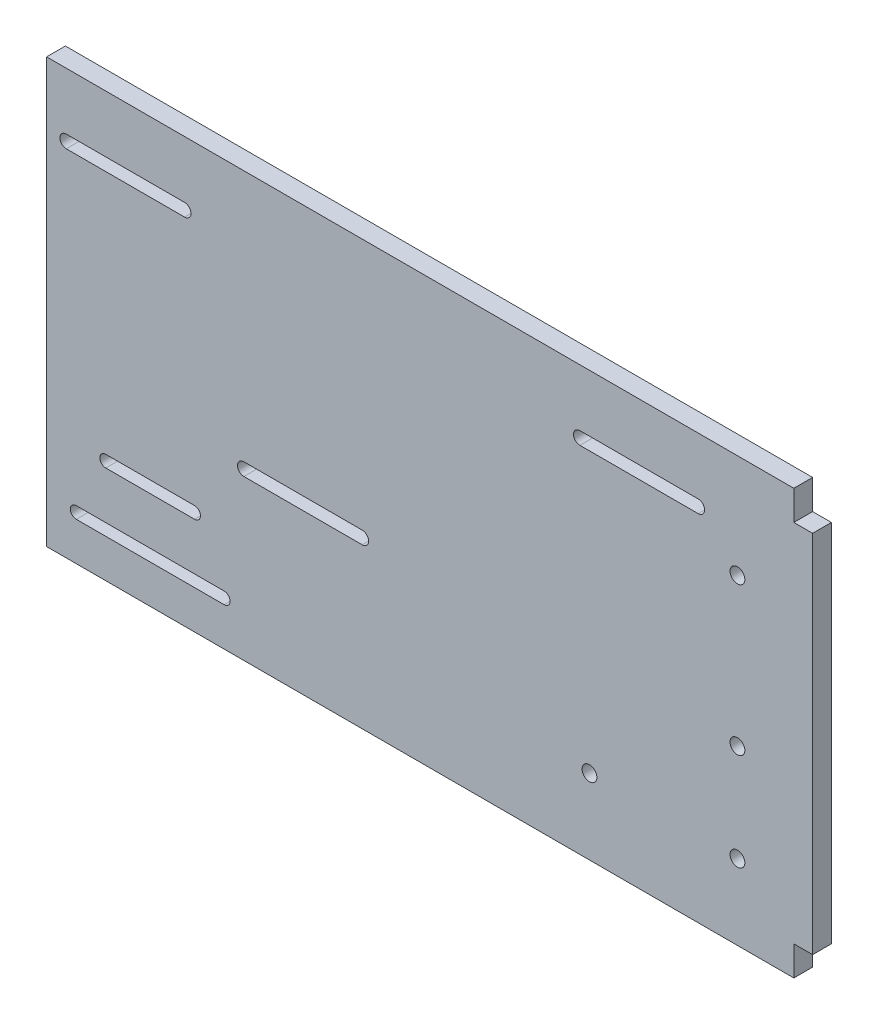
SolidWorks part; units mm, degrees
ref_plane "Front Plane" through (0, 0, 0) normal (0, 0, 1) x (1, 0, 0)
ref_plane "Top Plane" through (0, 0, 0) normal (0, 1, 0) x (1, 0, 0)
ref_plane "Right Plane" through (0, 0, 0) normal (1, 0, 0) x (0, 0, -1)
sketch "Sketch1" plane through (0, 0, 0) normal (0, 0, 1) x (1, 0, 0)
  line L6 (201.8749, 11.6995) -> (153.9614, -58.0745)
  line L7 (-16.8983, 41.9627) -> (201.8749, 41.9627)
  line L8 (-16.8983, 41.9627) -> (-16.8983, -41.404)
  line L9 (67.0768, -58.0745) -> (153.9614, -58.0745)
  line L10 (201.8749, 41.9627) -> (201.8749, 11.6995)
  line L11 (-16.8983, -41.404) -> (67.0768, -41.404)
  line L12 (67.0768, -58.0745) -> (67.0768, -41.404)
  line L13 (235.9349, 52.2529) -> (235.9349, -6.9018) construction
  circle A3 centre (18.7386, 20.5357) radius 2.15
  circle A4 centre (192.2886, 20.5357) radius 2.15
  circle A5 centre (78.7486, -45.3543) radius 2.15
  point P14 (-16.8983, -209.404)
  point P21 (17.0917, -18.834)
  dimension "D14" = 4.3
  dimension "D15" = 4.3
  dimension "D16" = 4.3
  dimension "D1" = 218.7732
  dimension "D2" = 83.3667
  dimension "D3" = 35.6369
  dimension "D4" = 209.1869
  dimension "D5" = 21.427
  dimension "D6" = 87.317
  dimension "D7" = 100.0372
  dimension "D8" = 83.9751
  dimension "D9" = 30.2632
  dimension "D10" = 86.8846
  dimension "D11" = 95.6469
  dimension "D12" = 22.57
  dimension "D13" = 33.99
  dimension "D17" = 34.06
  dimension "D18" = 21.427
  dimension "D19" = 168
sketch "Sketch3" plane through (0, 0, 0) normal (0, 0, 1) x (1, 0, 0)
  line L0 (235.9349, 52.2529) -> (235.9349, -6.9018) construction
  line L1 (235.9349, 52.2529) -> (235.9349, -6.9018) construction
  line L2 (58.7486, -43.2043) -> (98.7486, -43.2043)
  line L3 (244.5849, 41.9627) -> (-7.9083, 41.9627)
  line L4 (250.9349, 31.9627) -> (250.9349, -91.3543)
  line L5 (244.5849, -101.3543) -> (-7.9083, -101.3543)
  line L6 (-7.9083, 41.9627) -> (-7.9083, -101.3543)
  line L7 (17.0917, -86.3543) -> (37.0917, -86.3543) construction
  line L8 (-16.8983, 41.9627) -> (201.8749, 41.9627) construction
  line L9 (-1.2614, 22.6857) -> (38.7386, 22.6857)
  line L14 (-1.2614, 18.3857) -> (38.7386, 18.3857)
  line L15 (58.7486, -47.5043) -> (98.7486, -47.5043)
  line L16 (172.2886, 22.6857) -> (212.2886, 22.6857)
  line L17 (172.2886, 18.3857) -> (212.2886, 18.3857)
  line L18 (141.1766, -87.3543) -> (217.4403, -87.3543) construction
  line L19 (244.5849, 31.9586) -> (244.5849, -45.3543) construction
  line L20 (7.0917, -245.3543) -> (47.0917, -245.3543) construction
  line L21 (7.0917, -245.3543) -> (7.0917, -56.3543) construction
  line L22 (7.0917, -56.3543) -> (47.0917, -56.3543) construction
  line L23 (47.0917, -245.3543) -> (47.0917, -56.3543) construction
  line L24 (12.0917, -64.3543) -> (42.0917, -64.3543)
  line L25 (12.0917, -68.3543) -> (42.0917, -68.3543)
  line L40 (2.0917, -84.3543) -> (52.0917, -84.3543)
  line L41 (2.0917, -88.3543) -> (52.0917, -88.3543)
  line L45 (250.9349, 31.9627) -> (244.5849, 31.9627)
  line L46 (244.5849, 41.9627) -> (244.5849, 31.9627)
  line L49 (250.9349, -91.3543) -> (244.5849, -91.3543)
  line L50 (244.5849, -101.3543) -> (244.5849, -91.3543)
  circle A0 centre (78.7486, -45.3543) radius 2.15 construction
  circle A1 centre (192.2886, 20.5357) radius 2.15 construction
  circle A2 centre (18.7386, 20.5357) radius 2.15 construction
  circle A3 centre (78.7486, -45.3543) radius 2.15 construction
  circle A4 centre (192.2886, 20.5357) radius 2.15 construction
  circle A5 centre (18.7386, 20.5357) radius 2.15 construction
  arc A6 (-1.2614, 22.6857) -> (-1.2614, 18.3857) centre (-1.2614, 20.5357) ccw
  arc A7 (38.7386, 22.6857) -> (38.7386, 18.3857) centre (38.7386, 20.5357) cw
  arc A8 (58.7486, -43.2043) -> (58.7486, -47.5043) centre (58.7486, -45.3543) ccw
  arc A9 (98.7486, -43.2043) -> (98.7486, -47.5043) centre (98.7486, -45.3543) cw
  arc A10 (172.2886, 22.6857) -> (172.2886, 18.3857) centre (172.2886, 20.5357) ccw
  arc A11 (212.2886, 22.6857) -> (212.2886, 18.3857) centre (212.2886, 20.5357) cw
  circle A12 centre (17.0917, -86.3543) radius 2 construction
  circle A13 centre (37.0917, -86.3543) radius 2 construction
  circle A14 centre (27.0917, -66.3543) radius 2 construction
  circle A15 centre (225.5349, -43.0373) radius 2.5
  circle A17 centre (225.5349, 6.9627) radius 2.5
  circle A19 centre (225.5349, -75.9543) radius 2.5
  circle A21 centre (175.5349, -75.9543) radius 2.5
  arc A22 (12.0917, -68.3543) -> (12.0917, -64.3543) centre (12.0917, -66.3543) cw
  arc A23 (42.0917, -68.3543) -> (42.0917, -64.3543) centre (42.0917, -66.3543) ccw
  arc A24 (2.0917, -84.3543) -> (2.0917, -88.3543) centre (2.0917, -86.3543) ccw
  arc A25 (52.0917, -88.3543) -> (52.0917, -84.3543) centre (52.0917, -86.3543) ccw
  point P32 (18.7386, 18.3857)
  point P46 (192.2886, 22.6857)
  point P49 (78.7486, -43.2043)
  point P57 (17.0917, -18.834)
  point P62 (27.0917, -56.3543)
  point P65 (27.0917, -86.3543)
  point P70 (27.0917, -64.3543)
  dimension "D8" = 4
  dimension "D9" = 4
  dimension "D18" = 4
  dimension "D15" = 5
  dimension "D16" = 5
  dimension "D24" = 5
  dimension "D25" = 5
  dimension "D1" = 15
  dimension "D4" = 40
  dimension "D5" = 40
  dimension "D6" = 40
  dimension "D7" = 42
  dimension "D2" = 25
  dimension "D3" = 15
  dimension "D10" = 14
  dimension "D11" = 15
  dimension "D12" = 20
  dimension "D19" = 20
  dimension "D20" = 40
  dimension "D21" = 10
  dimension "D13" = 200
  dimension "D14" = 6.35
  dimension "D17" = 50
  dimension "D22" = 19.05
  dimension "D26" = 25.4
  dimension "D27" = 50
  dimension "D23" = 35
  dimension "D28" = 10
  dimension "D29" = 30
  dimension "D30" = 15
  dimension "D31" = 15
  dimension "D32" = 10
  dimension "D33" = 6.35
  dimension "D34" = 6.35
  dimension "D35" = 10
extrude "Boss-Extrude1" add sketch "Sketch3" along normal blind 6.35
equation "\"D15@Sketch1\"=\"D14@Sketch1\""
equation "\"D16@Sketch1\"=\"D14@Sketch1\""
equation "\"D5@Sketch3\"=\"D4@Sketch3\""
equation "\"D6@Sketch3\"=\"D4@Sketch3\""
equation "\"D9@Sketch3\"=\"D8@Sketch3\""
equation "\"D11@Sketch3\"=\"D3@Sketch3\""
equation "\"D18@Sketch3\"=\"D8@Sketch3\""
